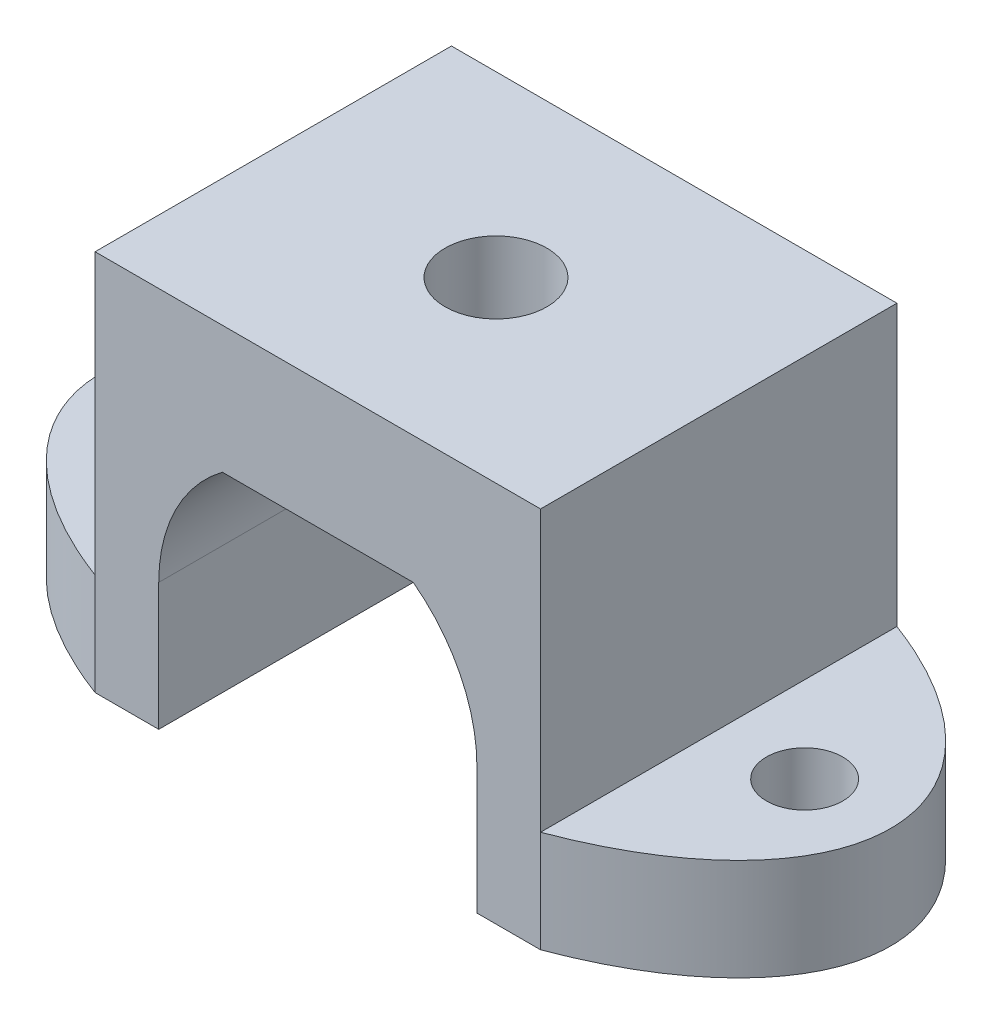
SolidWorks part; units mm, degrees
ref_plane "Plan de face" through (0, 0, 0) normal (0, 0, 1) x (1, 0, 0)
ref_plane "Plan de dessus" through (0, 0, 0) normal (0, 1, 0) x (1, 0, 0)
ref_plane "Plan de droite" through (0, 0, 0) normal (1, 0, 0) x (0, 0, -1)
sketch "Esquisse1" plane through (0, 0, 0) normal (0, 0, 1) x (1, 0, 0)
  line L0 (-15.5, 0) -> (-6.25, 0)
  line L1 (15.5, 0) -> (15.5, 4)
  line L2 (15.5, 4) -> (8.75, 4)
  line L3 (8.75, 4) -> (8.75, 15)
  line L4 (8.75, 15) -> (-8.75, 15)
  line L5 (-8.75, 15) -> (-8.75, 4)
  line L6 (-8.75, 4) -> (-15.5, 4)
  line L7 (-15.5, 4) -> (-15.5, 0)
  line L8 (-6.25, 5) -> (-6.25, 0)
  line L9 (-3.75, 10) -> (3.75, 10)
  line L10 (6.25, 0) -> (15.5, 0)
  line L11 (6.25, 5) -> (6.25, 0)
  line L12 (0, 10) -> (0, 0) construction
  arc A0 (-3.75, 10) -> (-6.25, 5) centre (0, 5) ccw
  arc A1 (6.25, 5) -> (3.75, 10) centre (0, 5) ccw
  dimension "D1" = 10
  dimension "D2" = 12.5
  dimension "D3" = 31
  dimension "D4" = 4
  dimension "D5" = 2.5
  dimension "D6" = 5
extrude "Boss.-Extru.1" add sketch "Esquisse1" along normal mid plane 14
sketch "Esquisse3" plane through (0, 4, 0) normal (0, 1, 0) x (1, 0, 0)
  line L0 (0, 0) -> (0, 11.5015) construction
  line L1 (-15.5, 7) -> (-8.75, -7) construction
  circle A0 centre (-12.125, 0) radius 1.5
  circle A1 centre (12.125, 0) radius 1.5
  point P9 (-12.125, 0)
  dimension "D1" = 3
extrude "Enlèv. mat.-Extru.2" cut sketch "Esquisse3" against normal blind 8.5
sketch "Esquisse4" plane through (0, 15, 0) normal (0, 1, 0) x (1, 0, 0)
  circle A0 centre (0, 0) radius 2
  dimension "D1" = 4
extrude "Enlèv. mat.-Extru.3" cut sketch "Esquisse4" against normal through all
sketch "Esquisse5" plane through (0, 4, 0) normal (0, 1, 0) x (1, 0, 0)
  line L0 (15.5, -7) -> (15.5, 7) construction
  line L1 (-8.75, 7) -> (-15.5, 7) construction
  line L2 (-15.5, -7) -> (-15.5, 7) construction
  line L3 (-8.75, -7) -> (-15.5, -7) construction
  line L4 (15.5, -7) -> (8.75, -7) construction
  line L5 (15.5, 7) -> (8.75, 7) construction
  line L6 (-8.75, 7) -> (-15.5, 7)
  line L7 (-15.5, -7) -> (-15.5, 7)
  line L8 (-8.75, -7) -> (-15.5, -7)
  line L9 (15.5, -7) -> (8.75, -7)
  line L10 (15.5, -7) -> (15.5, 7)
  line L11 (15.5, 7) -> (8.75, 7)
  circle A2 centre (12.125, 0) radius 2.75 construction
  ellipse E0 centre (0, 0) end of major axis (15.5, 0) minor radius 8.4805
  point P10 (0, 9.685)
  dimension "D1" = 5.5
extrude "Enlèv. mat.-Extru.4" cut sketch "Esquisse5" against normal through all contours E0 L10 L1 | E0 L3 L4 | E0 L7 L8 | E0 L6 L7
